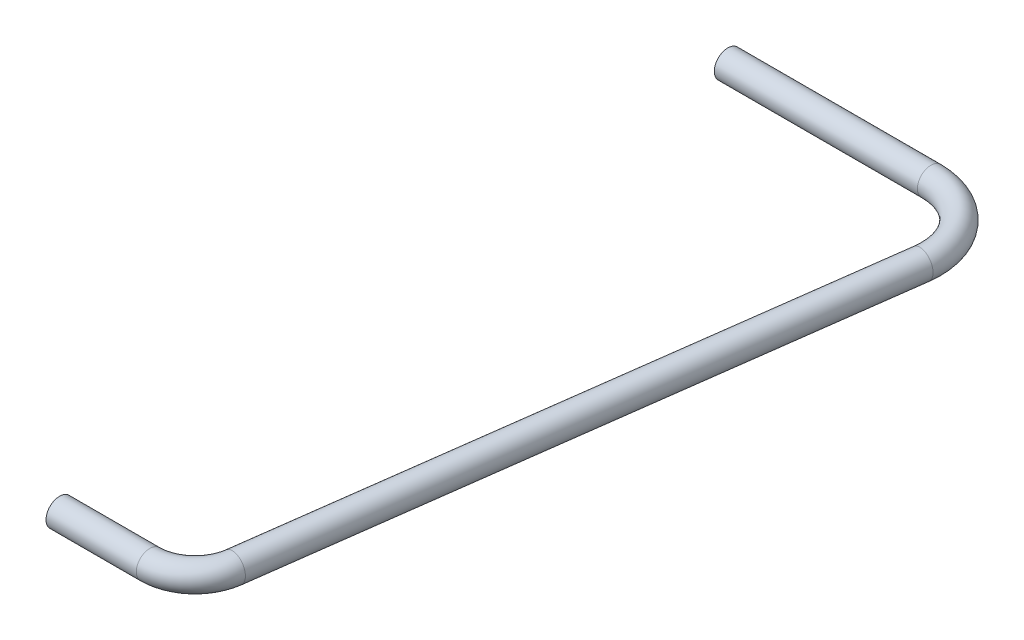
SolidWorks part; units mm, degrees
ref_plane "Front Plane" through (0, 0, 0) normal (0, 0, 1) x (1, 0, 0)
ref_plane "Top Plane" through (0, 0, 0) normal (0, 1, 0) x (1, 0, 0)
ref_plane "Right Plane" through (0, 0, 0) normal (1, 0, 0) x (0, 0, -1)
sketch "Sketch1" plane through (0, 0, 0) normal (0, 1, 0) x (1, 0, 0)
  line L0 (-0.5725, 78.5923) -> (-12.5725, 78.5923) construction
  line L1 (-0.5725, 78.5923) -> (19.4275, 78.5923)
  line L2 (29.3394, 87.2675) -> (47.2953, 221.605)
  line L3 (32.4275, 238.5923) -> (-12.5725, 238.5923)
  line L4 (-12.5725, 78.5923) -> (-12.5725, 238.5923) construction
  arc A0 (47.2953, 221.605) -> (32.4275, 238.5923) centre (32.4275, 223.5923) ccw
  arc A1 (29.3394, 87.2675) -> (19.4275, 78.5923) centre (19.4275, 88.5923) cw
  point P3 (-12.5725, 78.5923)
  point P11 (28.1799, 78.5923)
  dimension "D1" = 15
  dimension "D2" = 20
  dimension "D3" = 10
  dimension "D4" = 45
  dimension "D5" = 160
  dimension "D6" = 12
sweep "Sweep1" add path "Sketch1" circular profile diameter 6 parameters "D3"=6
